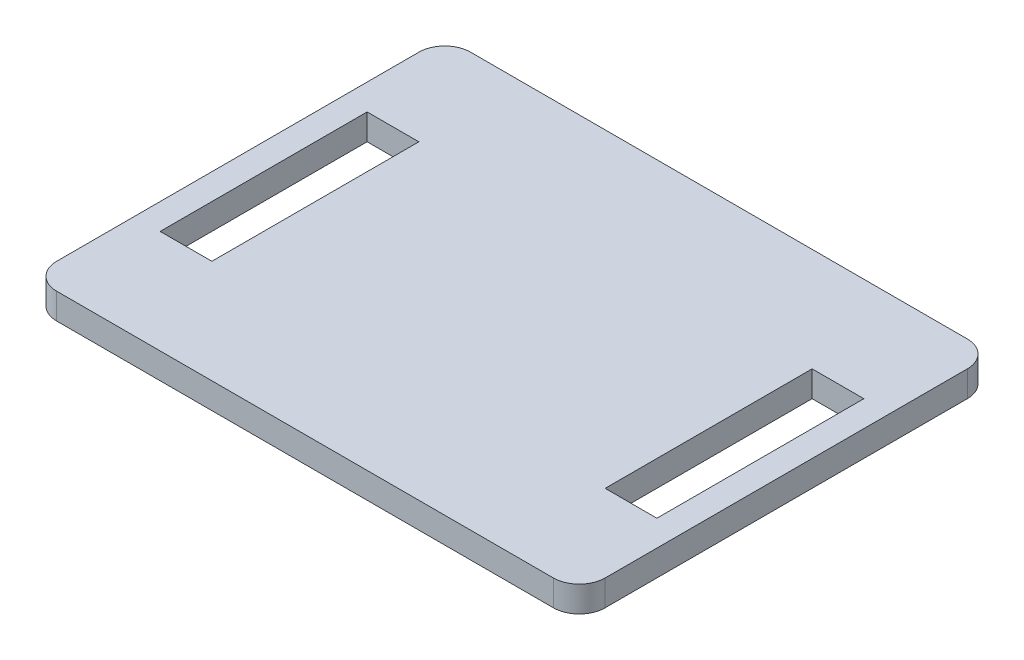
SolidWorks part; units mm, degrees
material "Mahogany"
ref_plane "Front Plane" through (0, 0, 0) normal (0, 0, 1) x (1, 0, 0)
ref_plane "Top Plane" through (0, 0, 0) normal (0, 1, 0) x (1, 0, 0)
ref_plane "Right Plane" through (0, 0, 0) normal (1, 0, 0) x (0, 0, -1)
sketch "Sketch1" plane through (0, 0, 0) normal (0, 1, 0) x (1, 0, 0)
  line L0 (0, 9.1341) -> (0, -9.1341) construction
  line L1 (-26.5, -20) -> (26.5, -20)
  line L2 (-26.5, -20) -> (-26.5, 20)
  line L3 (-26.5, 20) -> (26.5, 20)
  line L4 (26.5, -20) -> (26.5, 20)
  line L5 (-26.5, -20) -> (26.5, 20) construction
  line L6 (-26.5, 20) -> (26.5, -20) construction
  line L7 (-24, -10) -> (-19, -10)
  line L8 (-24, -10) -> (-24, 10)
  line L9 (-24, 10) -> (-19, 10)
  line L10 (-19, -10) -> (-19, 10)
  line L11 (-24, -10) -> (-19, 10) construction
  line L12 (-24, 10) -> (-19, -10) construction
  line L13 (24, 10) -> (19, 10)
  line L14 (19, -10) -> (19, 10)
  line L15 (24, -10) -> (19, -10)
  line L16 (24, -10) -> (24, 10)
  point P0 (0, 0)
  point P6 (-21.5, 0)
  dimension "D1" = 53
  dimension "D2" = 40
  dimension "D3" = 20
  dimension "D4" = 5
  dimension "D5" = 38
extrude "Boss-Extrude1" add sketch "Sketch1" along normal blind 2.5
fillet "Fillet1" radius 2.5 4 edges at (26.5, 1.25, 20) (-26.5, 1.25, -20) (26.5, 1.25, -20) (-26.5, 1.25, 20)
